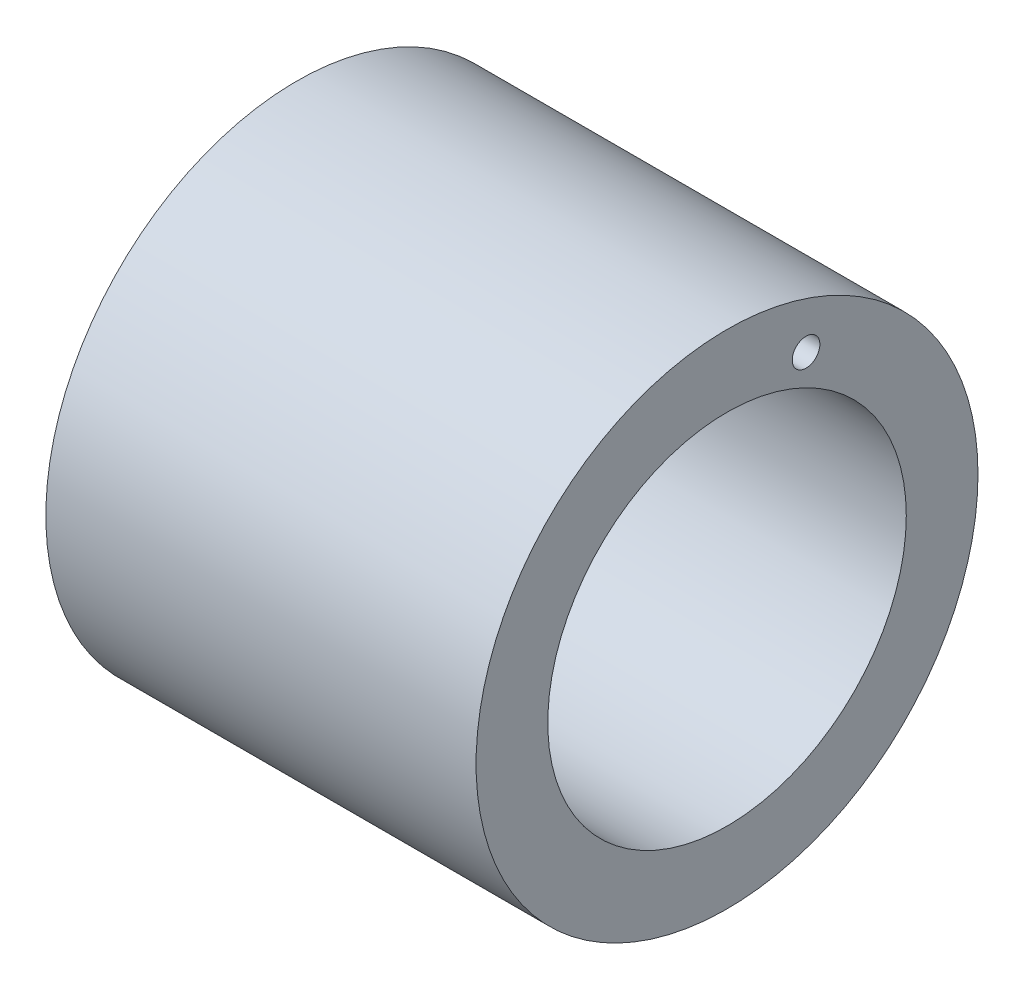
SolidWorks part; units mm, degrees
ref_plane "Front Plane" through (0, 0, 0) normal (0, 0, 1) x (1, 0, 0)
ref_plane "Top Plane" through (0, 0, 0) normal (0, 1, 0) x (1, 0, 0)
ref_plane "Right Plane" through (0, 0, 0) normal (1, 0, 0) x (0, 0, -1)
sketch "Sketch1" plane through (0, 0, 0) normal (1, 0, 0) x (0, 0, -1)
  circle A0 centre (0, 0) radius 10
  dimension "D1" = 20
extrude "Extrude-Thin1" add sketch "Sketch1" along normal blind 24 thin
sketch "Sketch2" plane through (24, 0, 0) normal (1, 0, 0) x (0, 0, -1)
  circle A0 centre (4.4079, 10.693) radius 0.7707
extrude "Cut-Extrude1" cut sketch "Sketch2" against normal blind 10
